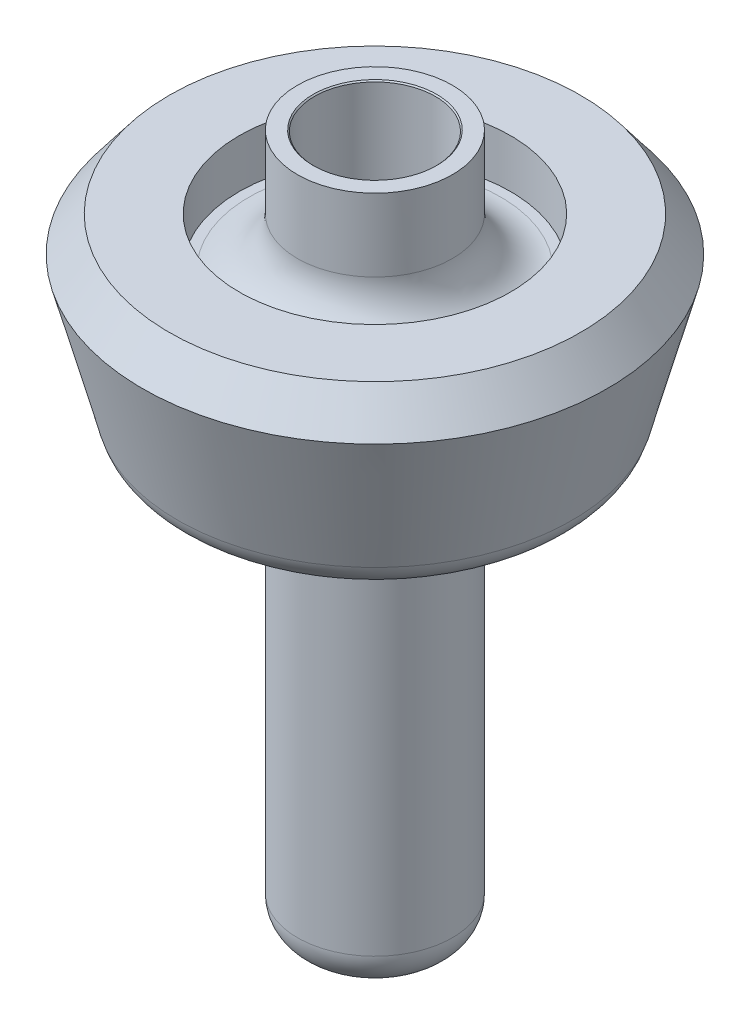
SolidWorks part; units mm, degrees
ref_plane "Front Plane" through (0, 0, 0) normal (0, 0, 1) x (1, 0, 0)
ref_plane "Top Plane" through (0, 0, 0) normal (0, 1, 0) x (1, 0, 0)
ref_plane "Right Plane" through (0, 0, 0) normal (1, 0, 0) x (0, 0, -1)
sketch "Sketch1" plane through (0, 0, 0) normal (0, 0, 1) x (1, 0, 0)
  line L0 (0, 17.7986) -> (0, 0.08) construction
  line L1 (1.6, 15) -> (1.6, 12.5)
  line L2 (1.6, 12.5) -> (2.8, 12.5)
  line L3 (2.8, 12.5) -> (2.8, 13.5)
  line L4 (2.8, 13.5) -> (4.2441, 13.5)
  line L5 (4.8, 12.7756) -> (4.0713, 10.0559)
  line L6 (3.3468, 9.5) -> (2.35, 9.5)
  line L7 (1.6, 8.75) -> (1.6, 1.3568)
  line L8 (1.225, 0.7073) -> (0.2586, 0.1493)
  line L9 (1.6, 15) -> (0, 15)
  line L10 (4.2441, 13.5) -> (4.8, 12.7756)
  line L11 (0, 0.08) -> (0, 15)
  line L12 (0, 0.08) -> (-0.2923, 0.08) construction
  line L13 (0, 0) -> (0, -7.913) construction
  arc A0 (4.0713, 10.0559) -> (3.3468, 9.5) centre (3.3468, 10.25) cw
  arc A1 (2.35, 9.5) -> (1.6, 8.75) centre (2.35, 8.75) ccw
  arc A2 (1.6, 1.3568) -> (1.225, 0.7073) centre (0.85, 1.3568) cw
  arc A3 (0, 0.08) -> (0.2586, 0.1493) centre (0, 0.5971) ccw
  point P8 (4.9941, 13.5)
  dimension "D11" = 0.75
  dimension "D12" = 0.75
  dimension "D1" = 15
  dimension "D2" = 2.5
  dimension "D3" = 1.6
  dimension "D4" = 120
  dimension "D5" = 1.6
  dimension "D6" = 105
  dimension "D7" = 3
  dimension "D8" = 1.2
  dimension "D9" = 4.8
  dimension "D10" = 1
  dimension "D13" = 0.08
revolve "Revolve1" add sketch "Sketch1" angle 360 about L0
fillet "Fillet1" radius 1 1 edges at (-1.6, 12.5, 0)
hole_wizard "Ø2.5mm Dowel Hole1" positions "Sketch2" profile "Sketch4" hole size "Ø2.5" standard "ISO"
sketch "Sketch2" plane through (0, 15, 0) normal (0, 1, 0) x (1, 0, 0)
  point P0 (0, 0)
sketch "Sketch4" plane through (0, 15, 0) normal (1, 0, 0) x (0, 0, 1)
  line L0 (0, 0) -> (0, 6.2511)
  line L1 (0, 6.2511) -> (1.25, 5.5)
  line L2 (1.25, 5.5) -> (1.25, 0.025)
  line L3 (1.25, 0.025) -> (1.275, 0)
  line L5 (1.275, 0) -> (0, 0)
  line L6 (-1.25, 0.025) -> (-1.275, 0) construction
  line L10 (0, 6.2511) -> (-1.25, 5.5) construction
  line L11 (0, -6.35) -> (0, 107.95) construction
  dimension "Hole Dia." = 2.5
  dimension "Hole Depth" = 5.5
  dimension "Near C'Sink Dia." = 2.55
  dimension "Near C'Sink Angle" = 90
  dimension "Drill Angle" = 118
ref_plane "Plane1" through (0, 12.5, 0) normal (0, 1, 0) x (1, 0, 0)
